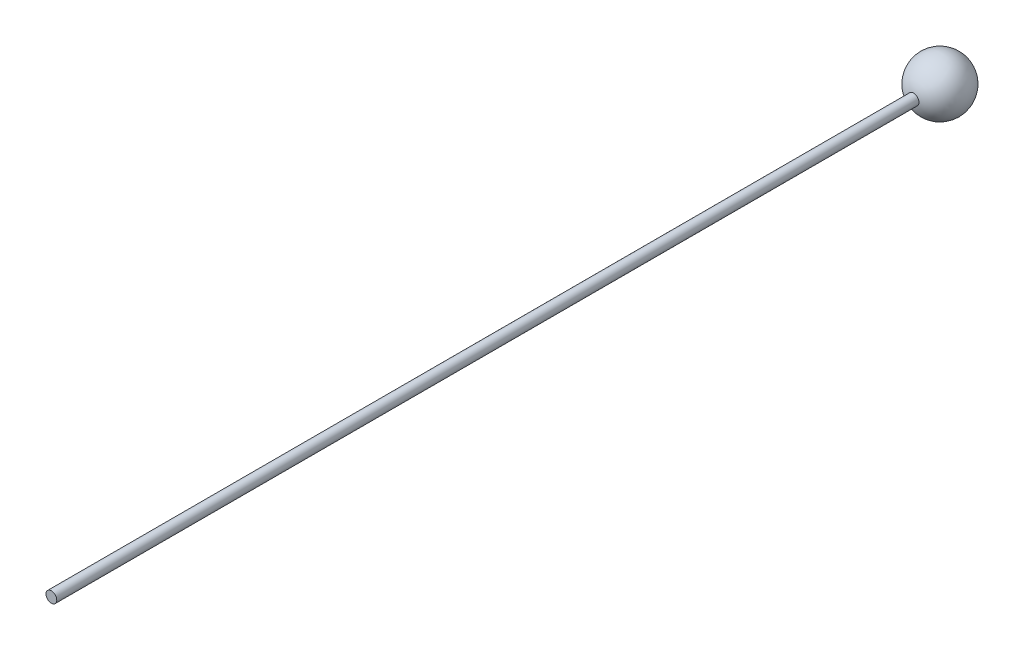
SolidWorks part; units mm, degrees
ref_plane "Plano frontal" through (0, 0, 0) normal (1, 0, 0) x (0, 1, 0)
ref_plane "Plano superior" through (0, 0, 0) normal (0, 0, 1) x (0, 1, 0)
ref_plane "Plano direito" through (0, 0, 0) normal (0, 1, 0) x (-1, 0, 0)
sketch "Esboço3" plane through (0, 0, 0) normal (0, 1, 0) x (-1, 0, 0)
  line L0 (0, 0) -> (0, -80) construction
  line L1 (0, -80) -> (0, -85)
  arc A0 (0, -85) -> (0, -80) centre (0, -82.5) ccw
revolve "Revolução1" add sketch "Esboço3" angle 360 about L1
sketch "Esboço4" plane through (0, 0, 0) normal (0, 0, 1) x (0, 1, 0)
  circle A0 centre (0, 0) radius 0.5
extrude "Ressalto-extrusão1" add sketch "Esboço4" against normal up to body
